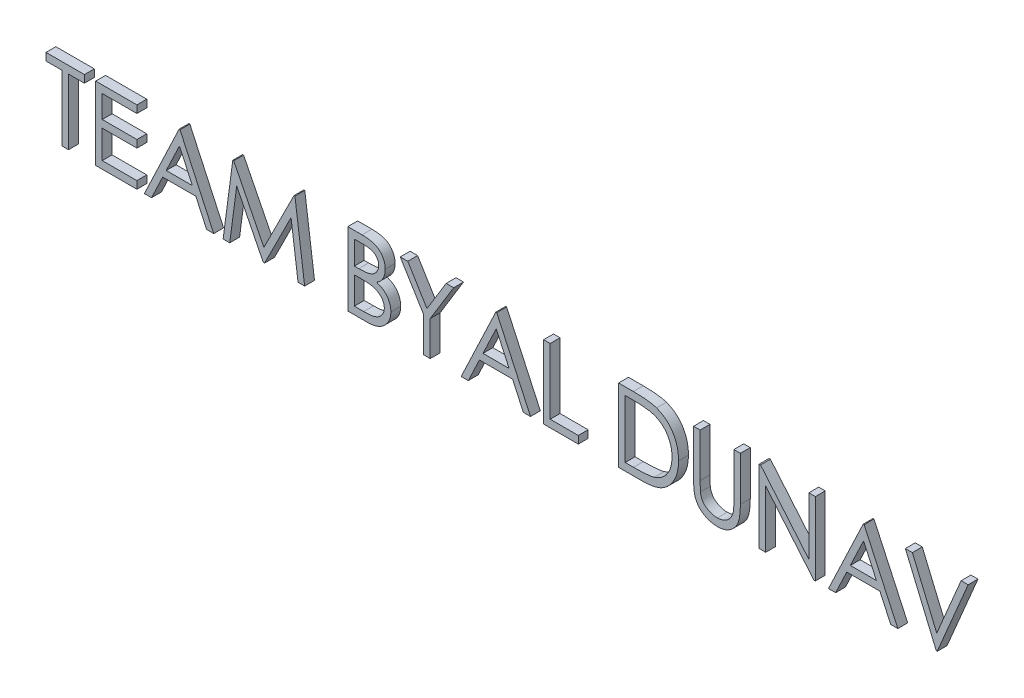
SolidWorks part; units mm, degrees
ref_plane "Front Plane" through (0, 0, 0) normal (0, 0, 1) x (1, 0, 0)
ref_plane "Top Plane" through (0, 0, 0) normal (0, 1, 0) x (1, 0, 0)
ref_plane "Right Plane" through (0, 0, 0) normal (1, 0, 0) x (0, 0, -1)
sketch "Sketch1" plane through (0, 0, 0) normal (0, 0, 1) x (1, 0, 0)
  line L0 (-69.3728, 0) -> (42.6948, 0) construction
  text T0 "TEAM BYAL DUNAV" font "Century Gothic" height in points 28
extrude "Boss-Extrude1" add sketch "Sketch1" along normal blind 1
